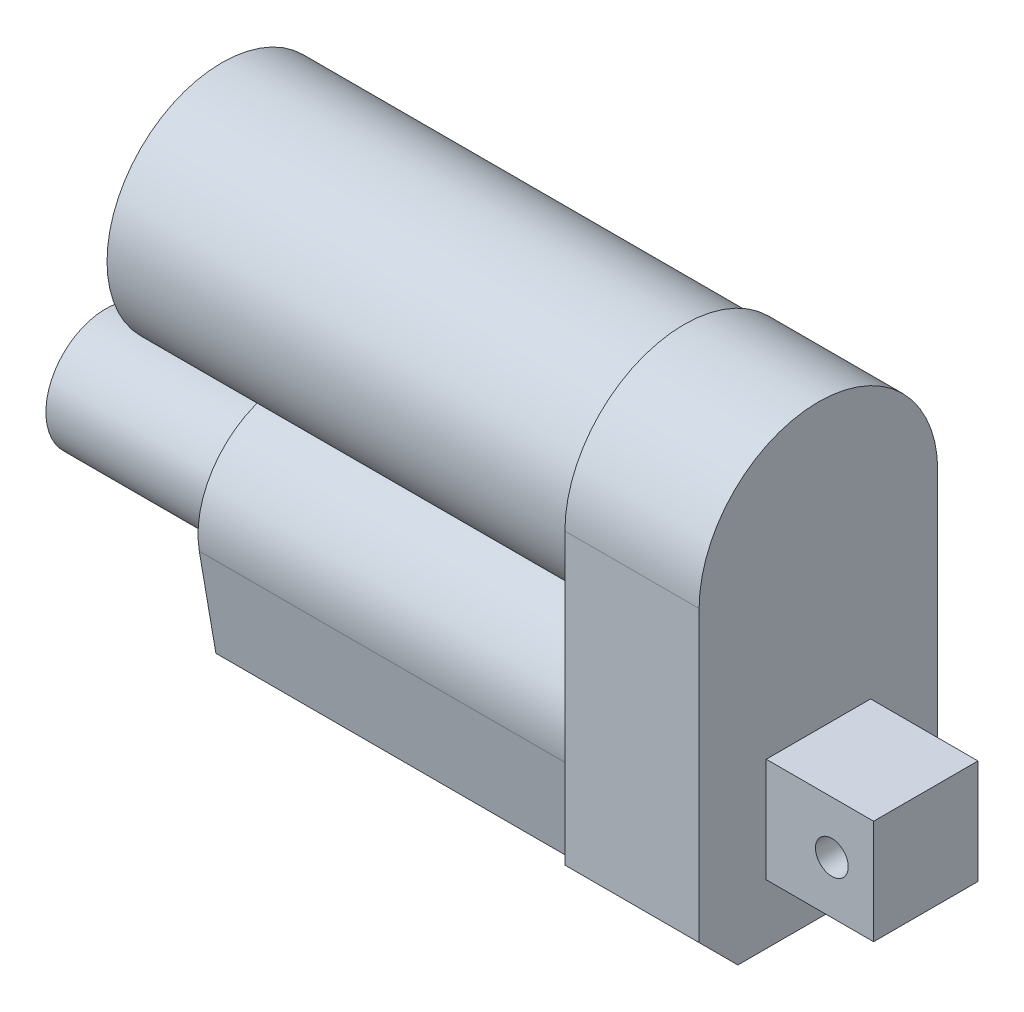
SolidWorks part; units mm, degrees
ref_plane "Front Plane" through (0, 0, 0) normal (0, 0, 1) x (1, 0, 0)
ref_plane "Top Plane" through (0, 0, 0) normal (0, 1, 0) x (1, 0, 0)
ref_plane "Right Plane" through (0, 0, 0) normal (1, 0, 0) x (0, 0, -1)
sketch "Sketch1" plane through (0, 0, 0) normal (1, 0, 0) x (0, 0, -1)
  line L0 (-20, 36.25) -> (-20, -18.75)
  line L1 (-20, -18.75) -> (20, -18.75)
  line L2 (20, -18.75) -> (20, 36.25)
  line L3 (0, -18.75) -> (0, 56.25) construction
  line L4 (-20, -12.25) -> (-13.5, -18.75)
  line L5 (20, -12.25) -> (13.5, -18.75)
  line L6 (-8.75, -8.75) -> (8.75, 8.75) construction
  line L7 (-8.75, 8.75) -> (8.75, 8.75) construction
  line L8 (-8.75, 8.75) -> (-8.75, -8.75) construction
  line L9 (-8.75, -8.75) -> (8.75, -8.75) construction
  line L10 (8.75, 8.75) -> (8.75, -8.75) construction
  circle A0 centre (0, 36.25) radius 20
  point P12 (0, 0)
  point P17 (0, 0)
  point P19 (0, 0)
  dimension "D1" = 40
  dimension "D2" = 75
  dimension "D3" = 6.5
  dimension "D4" = 45
  dimension "D5" = 65
  dimension "D6" = 17.5
extrude "Boss-Extrude1" add sketch "Sketch1" along normal blind 22.5 contours A0 | A0 L0 L4 L1 L5 L2
sketch "Sketch3" plane through (22.5, 0, 0) normal (1, 0, 0) x (0, 0, -1)
  line L1 (8.75, 8.75) -> (-8.75, 8.75)
  line L2 (8.75, 8.75) -> (8.75, -8.75)
  line L3 (8.75, -8.75) -> (-8.75, -8.75)
  line L4 (-8.75, 8.75) -> (-8.75, -8.75)
  point P4 (0, 0)
  point P7 (0, 0)
extrude "Boss-Extrude2" add sketch "Sketch3" along normal blind 18
sketch "Sketch4" plane through (0, 0, 8.75) normal (0, 0, 1) x (1, 0, 0)
  line L0 (40.5, 0) -> (36.25, 0) construction
  line L1 (40.5, 8.75) -> (40.5, -8.75) construction
  line L2 (36.25, 0) -> (33.5, 0) construction
  circle A0 centre (33.5, 0) radius 2.75
  dimension "D1" = 5.5
  dimension "D2" = 7
extrude "Cut-Extrude1" cut sketch "Sketch4" against normal through all both and the other way through all
sketch "Sketch5" plane through (0, 0, 0) normal (-1, 0, 0) x (0, 0, 1)
  line L0 (-14.7836, -2.5385) -> (-12, -18.75)
  line L1 (-12, -18.75) -> (12, -18.75)
  line L2 (12, -18.75) -> (14.7836, -2.5385)
  line L3 (13.5, -18.75) -> (-13.5, -18.75) construction
  line L4 (0, 0) -> (0, -18.75) construction
  circle A0 centre (0, 0) radius 15
  point P5 (16.1765, 0)
  point P10 (-13.4656, -6.6088)
  point P11 (14.6773, -3.0947)
  dimension "D1" = 30
  dimension "D2" = 24
extrude "Boss-Extrude3" add sketch "Sketch5" along normal blind 66.5
sketch "Sketch6" plane through (0, 0, 0) normal (-1, 0, 0) x (0, 0, 1)
  circle A0 centre (0, 36.25) radius 19.25
  arc A1 (20, 36.25) -> (-20, 36.25) centre (0, 36.25) ccw construction
  dimension "D1" = 38.5
extrude "Boss-Extrude4" add sketch "Sketch6" along normal blind 77.5
sketch "Sketch7" plane through (-66.5, 0, 0) normal (-1, 0, 0) x (0, 0, 1)
  circle A0 centre (0, 0) radius 10
  dimension "D1" = 20
extrude "Boss-Extrude5" add sketch "Sketch7" along normal blind 30.5
